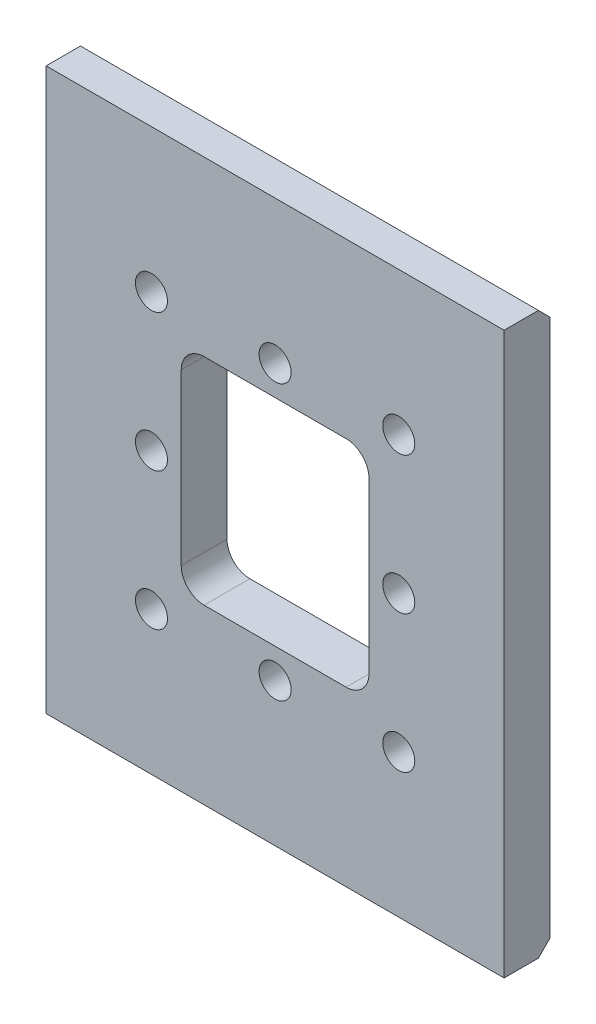
SolidWorks part; units mm, degrees
ref_plane "前视基准面" through (0, 0, 0) normal (0, 0, 1) x (1, 0, 0)
ref_plane "上视基准面" through (0, 0, 0) normal (0, 1, 0) x (1, 0, 0)
ref_plane "右视基准面" through (0, 0, 0) normal (1, 0, 0) x (0, 0, -1)
sketch "草图1" plane through (0, 0, 0) normal (0, 0, 1) x (1, 0, 0)
  line L1 (-100, 122.5) -> (100, 122.5)
  line L2 (-100, 122.5) -> (-100, -122.5)
  line L3 (-100, -122.5) -> (100, -122.5)
  line L4 (100, 122.5) -> (100, -122.5)
  line L5 (-100, 122.5) -> (100, -122.5) construction
  line L6 (-100, -122.5) -> (100, 122.5) construction
  point P0 (0, 0)
  dimension "D1" = 245
  dimension "D2" = 200
extrude "凸台-拉伸1" add sketch "草图1" along normal blind 20
sketch "草图2" plane through (0, 0, 20) normal (0, 0, 1) x (1, 0, 0)
  line L1 (-31, 47) -> (31, 47)
  line L2 (-41, 37) -> (-41, -37)
  line L3 (-31, -47) -> (31, -47)
  line L4 (41, 37) -> (41, -37)
  line L5 (-41, 47) -> (41, -47) construction
  line L6 (-41, -47) -> (41, 47) construction
  line L7 (100, 122.5) -> (-100, 122.5) construction
  line L8 (-100, 122.5) -> (-100, -122.5) construction
  arc A0 (-41, -37) -> (-31, -47) centre (-31, -37) ccw
  arc A1 (31, -47) -> (41, -37) centre (31, -37) ccw
  arc A2 (31, 47) -> (41, 37) centre (31, 37) cw
  arc A3 (-31, 47) -> (-41, 37) centre (-31, 37) ccw
  circle A4 centre (-54, 60) radius 7
  circle A5 centre (0, 60) radius 7
  circle A6 centre (54, 60) radius 7
  circle A7 centre (-54, 0) radius 7
  circle A8 centre (54, 0) radius 7
  circle A9 centre (-54, -60) radius 7
  circle A10 centre (0, -60) radius 7
  circle A11 centre (54, -60) radius 7
  point P0 (0, 0)
  point P34 (0, 0)
  point P35 (0, 0)
  point P36 (0, 0)
  point P37 (0, 0)
  point P38 (0, 0)
  point P39 (0, 0)
  point P40 (0, 0)
  point P41 (55.8398, -2.8136)
  point P42 (0, 0)
  point P43 (57.1384, 59.0863)
  dimension "D3" = 10
  dimension "D4" = 54
  dimension "D5" = 54
  dimension "D6" = 60
  dimension "D7" = 60
  dimension "D8" = 62.5
  dimension "D9" = 46
  dimension "D10" = 14
  dimension "D11" = 14
  dimension "D12" = 14
  dimension "D13" = 14
  dimension "D14" = 14
  dimension "D15" = 14
  dimension "D16" = 14
  dimension "D17" = 14
  dimension "D1" = 94
  dimension "D2" = 82
extrude "切除-拉伸1" cut sketch "草图2" against normal up to next
chamfer "倒角1" distance 5 angle 45 2 edges at (0, -122.5, 0) (0, 122.5, 0)
